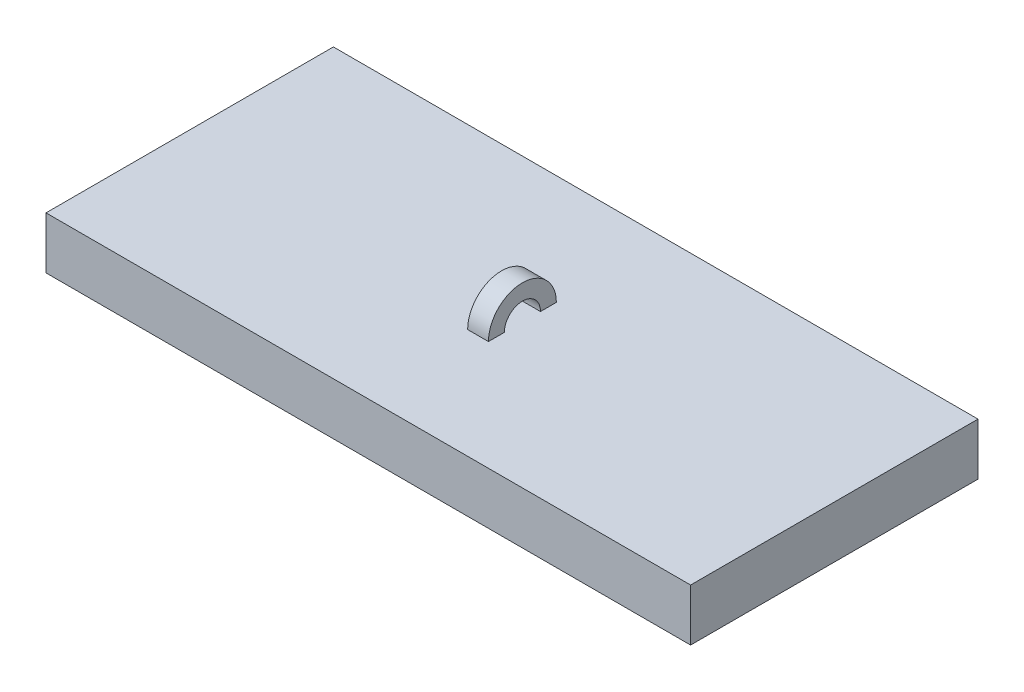
SolidWorks part; units mm, degrees
ref_plane "Front Plane" through (0, 0, 0) normal (0, 0, 1) x (1, 0, 0)
ref_plane "Top Plane" through (0, 0, 0) normal (0, 1, 0) x (1, 0, 0)
ref_plane "Right Plane" through (0, 0, 0) normal (1, 0, 0) x (0, 0, -1)
sketch "Sketch2" plane through (0, 0, 0) normal (0, 1, 0) x (1, 0, 0)
  line L1 (-61.9549, -27.6216) -> (61.9549, -27.6216)
  line L2 (-61.9549, -27.6216) -> (-61.9549, 27.6216)
  line L3 (-61.9549, 27.6216) -> (61.9549, 27.6216)
  line L4 (61.9549, -27.6216) -> (61.9549, 27.6216)
  line L5 (-61.9549, -27.6216) -> (61.9549, 27.6216) construction
  line L6 (-61.9549, 27.6216) -> (61.9549, -27.6216) construction
  point P0 (0, 0)
extrude "Boss-Extrude2" add sketch "Sketch2" along normal blind 10
sketch "Sketch3" plane through (0, 10, 0) normal (0, 1, 0) x (1, 0, 0)
  line L0 (-61.9549, 0) -> (61.9549, 0) construction
  line L1 (0, 27.6216) -> (0, -27.6216) construction
  line L3 (-2, 6.5271) -> (2, 6.5271)
  line L4 (61.9549, -27.6216) -> (61.9549, 27.6216)
  line L5 (61.9549, 27.6216) -> (-61.9549, 27.6216)
  line L6 (-61.9549, 27.6216) -> (-61.9549, -27.6216)
  line L7 (-61.9549, -27.6216) -> (61.9549, -27.6216)
  line L8 (61.9549, -27.6216) -> (61.9549, 27.6216)
  line L9 (61.9549, 27.6216) -> (-61.9549, 27.6216)
  line L10 (-61.9549, 27.6216) -> (-61.9549, -27.6216)
  line L11 (-61.9549, -27.6216) -> (61.9549, -27.6216)
  line L12 (-2, 6.5271) -> (-2, 3.4719)
  line L13 (-2, 3.4719) -> (2, 3.4719)
  line L14 (2, 6.5271) -> (2, 3.4719)
  point P12 (0, 6.5271)
  dimension "D2" = 4
  dimension "D1" = 0
revolve "Revolve4" add sketch "Sketch3" angle 180 about L0
ref_plane "Plane1" through (0, 16.5271, 0) normal (0, 1, 0) x (1, 0, 0)
sketch "Sketch4" plane through (0, 16.5271, 0) normal (0, 1, 0) x (1, 0, 0)
  line L0 (-2, 6.5271) -> (2, -6.5271) construction
  line L4 (-2, 6.5271) -> (-2, -6.5271)
  line L5 (-2, -6.5271) -> (2, -6.5271)
  line L6 (2, -6.5271) -> (2, 6.5271)
  line L7 (2, 6.5271) -> (-2, 6.5271)
  line L8 (-2, 6.5271) -> (-2, -6.5271)
  line L9 (-2, -6.5271) -> (2, -6.5271)
  line L10 (2, -6.5271) -> (2, 6.5271)
  line L11 (2, 6.5271) -> (-2, 6.5271)
  dimension "D1" = 0
